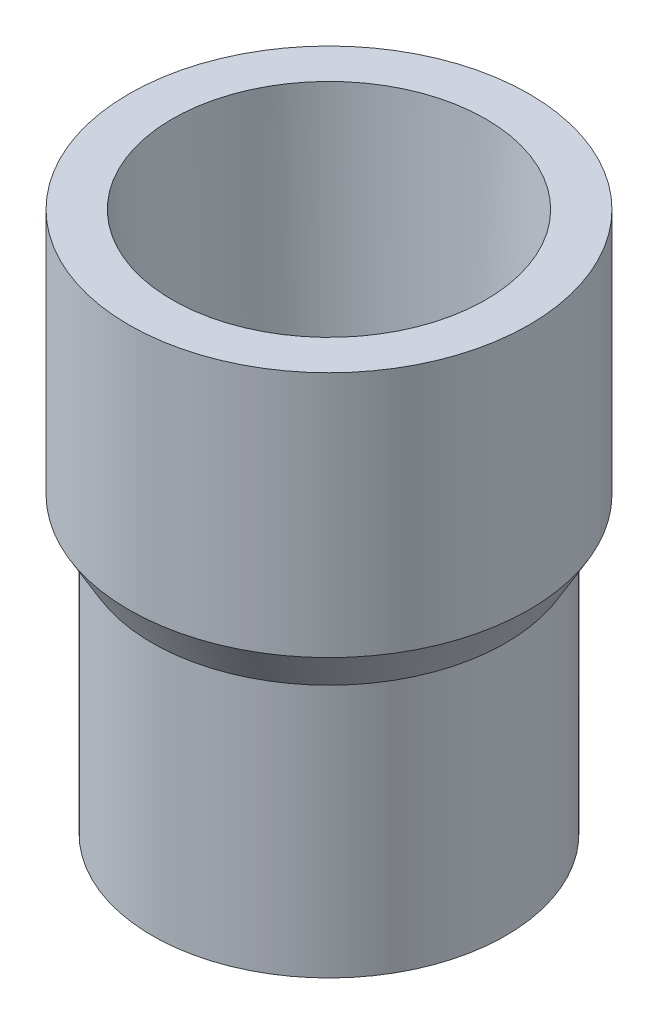
SolidWorks part; units mm, degrees
ref_plane "Front Plane" through (0, 0, 0) normal (0, 0, 1) x (1, 0, 0)
ref_plane "Top Plane" through (0, 0, 0) normal (0, 1, 0) x (1, 0, 0)
ref_plane "Right Plane" through (0, 0, 0) normal (1, 0, 0) x (0, 0, -1)
sketch "Sketch1" plane through (0, 0, 0) normal (0, 0, 1) x (1, 0, 0)
  line L0 (0, 0) -> (0, 3.0295) construction
  line L5 (9.8, 0.7152) -> (10.25, -14.2848)
  line L6 (10.25, -14.2848) -> (13.25, -14.2848)
  line L7 (13.25, -14.2848) -> (13.25, 4.7187)
  line L8 (13.25, 4.7187) -> (15, 7.7498)
  line L9 (15, 7.7498) -> (15, 26.2427)
  line L10 (15, 26.2427) -> (11.75, 26.2427)
  line L11 (11.75, 26.2427) -> (11, 6.2427)
  line L12 (11, 6.2427) -> (11, 1.2427)
  line L13 (11, 1.2427) -> (9.8, 1.2427)
  line L14 (9.8, 1.2427) -> (9.8, 0.7152)
  point P1 (0, 0)
  point P9 (0, 0)
  point P15 (2.8389, 4.7187)
  point P16 (0, 0)
  point P17 (3.8836, 5.7761)
  point P18 (2.8389, 11.1441)
  point P19 (0, 0)
  dimension "D1" = 22
  dimension "D2" = 23.5
  dimension "D3" = 20
  dimension "D4" = 30
  dimension "D5" = 5
  dimension "D6" = 0.5275
  dimension "D7" = 19.6
  dimension "D8" = 20.5
  dimension "D9" = 15
  dimension "D10" = 3
  dimension "D11" = 150
revolve "Revolve1" add sketch "Sketch1" angle 360 about L0
